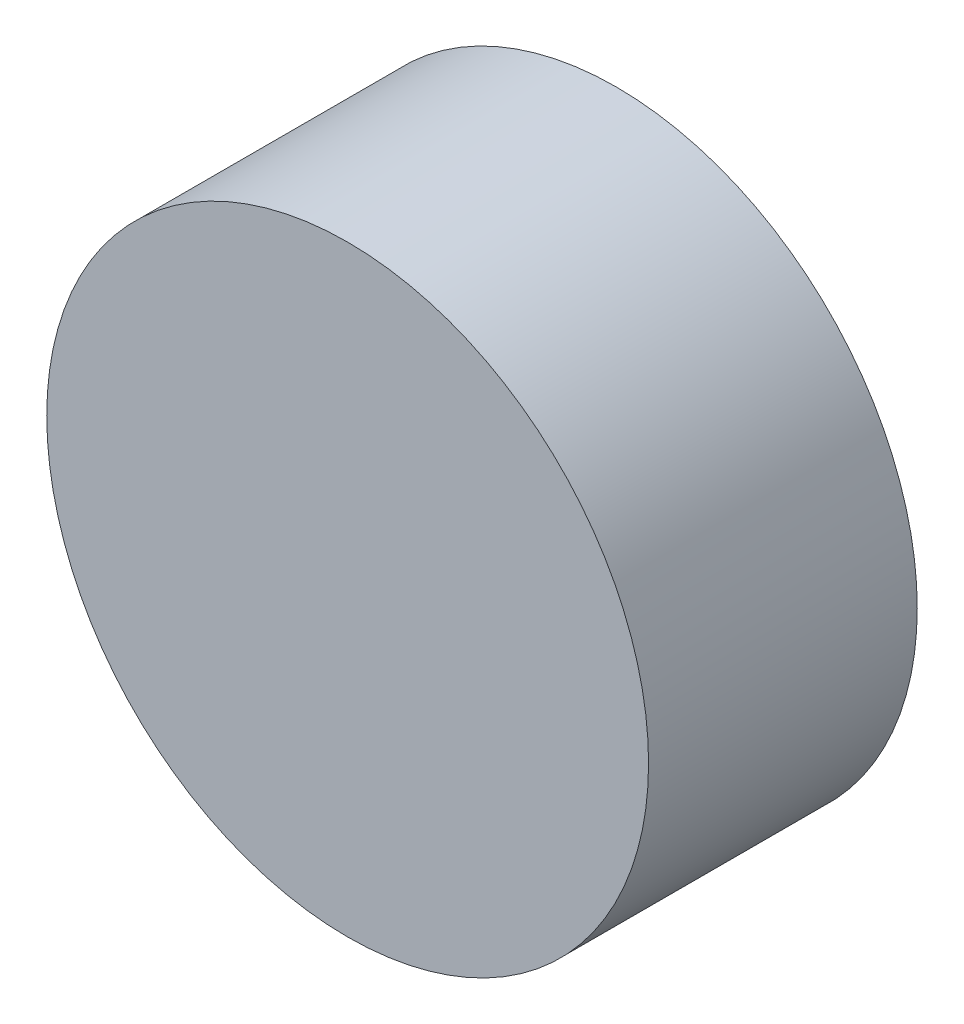
SolidWorks part; units mm, degrees
ref_plane "Front Plane" through (0, 0, 0) normal (0, 0, 1) x (1, 0, 0)
ref_plane "Top Plane" through (0, 0, 0) normal (0, 1, 0) x (1, 0, 0)
ref_plane "Right Plane" through (0, 0, 0) normal (1, 0, 0) x (0, 0, -1)
sketch "Sketch1" plane through (0, 0, 0) normal (0, 0, 1) x (1, 0, 0)
  circle A0 centre (0, 0) radius 11.2
extrude "Boss-Extrude1" add sketch "Sketch1" along normal blind 10
